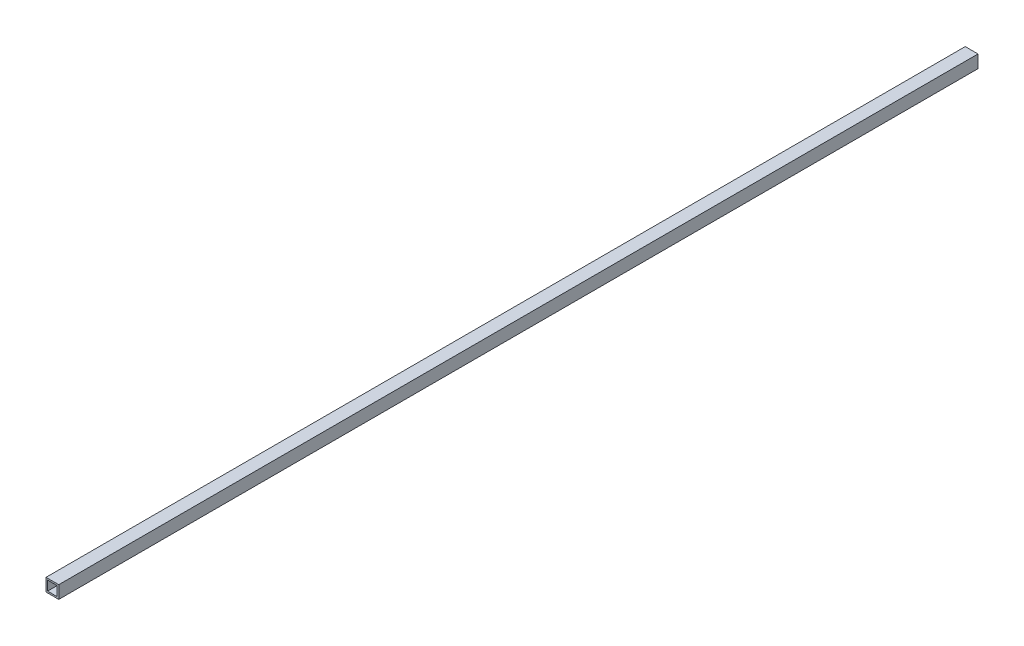
SolidWorks part; units mm, degrees
ref_plane "Front Plane" through (0, 0, 0) normal (0, 0, 1) x (1, 0, 0)
ref_plane "Top Plane" through (0, 0, 0) normal (0, 1, 0) x (1, 0, 0)
ref_plane "Right Plane" through (0, 0, 0) normal (1, 0, 0) x (0, 0, -1)
sketch "Sketch1" plane through (0, 0, 0) normal (0, 0, 1) x (1, 0, 0)
  line L0 (-4.7625, 4.7625) -> (4.7625, 4.7625)
  line L2 (-6.35, 6.35) -> (6.35, 6.35)
  line L3 (-6.35, 6.35) -> (-6.35, -6.35)
  line L4 (-6.35, -6.35) -> (6.35, -6.35)
  line L5 (6.35, 6.35) -> (6.35, -6.35)
  line L10 (4.7625, 4.7625) -> (4.7625, -4.7625)
  line L11 (-4.7625, -4.7625) -> (4.7625, -4.7625)
  line L12 (-4.7625, 4.7625) -> (-4.7625, -4.7625)
  point P12 (0, 6.35)
  point P14 (6.35, 0)
  dimension "Wall Thickness" = 1.5875
  dimension "Outside Width" = 12.7
  dimension "Outside Height" = 12.7
  dimension "Inside Height" = 9.525
  dimension "Inside Width" = 9.525
sketch "Sketch2" plane through (0, 0, 0) normal (1, 0, 0) x (0, 0, -1)
  line L0 (457.2, 0) -> (-457.2, 0)
  point P4 (0, 0)
  point P7 (-457.2, 0)
  point P10 (457.2, 0)
  dimension "Length" = 914.4
sketch "Sketch3" plane through (0, 0, 0) normal (0, 0, 1) x (1, 0, 0)
  line L21 (6.35, 6.35) -> (-6.35, 6.35)
  line L22 (6.35, -6.35) -> (6.35, 6.35)
  line L23 (-6.35, -6.35) -> (6.35, -6.35)
  line L24 (-6.35, 6.35) -> (-6.35, -6.35)
  line L25 (6.35, 6.35) -> (-6.35, 6.35)
  line L26 (6.35, -6.35) -> (6.35, 6.35)
  line L27 (-6.35, -6.35) -> (6.35, -6.35)
  line L28 (-6.35, 6.35) -> (-6.35, -6.35)
  line L29 (4.7625, 4.7625) -> (-4.7625, 4.7625)
  line L30 (4.7625, -4.7625) -> (4.7625, 4.7625)
  line L31 (-4.7625, -4.7625) -> (4.7625, -4.7625)
  line L32 (-4.7625, 4.7625) -> (-4.7625, -4.7625)
  line L33 (4.7625, 4.7625) -> (-4.7625, 4.7625)
  line L34 (4.7625, -4.7625) -> (4.7625, 4.7625)
  line L35 (-4.7625, -4.7625) -> (4.7625, -4.7625)
  line L36 (-4.7625, 4.7625) -> (-4.7625, -4.7625)
  dimension "D1" = 0
  dimension "D2" = 0
extrude "Boss-Extrude1" add sketch "Sketch3" along normal up to vertex (457.2 mm away) and the other way up to vertex (457.2 mm away) up to point (0, 0, 457.2) other way up to point (0, 0, -457.2)
sketch "Drawing Reference" plane through (0, 0, 0) normal (1, 0, 0) x (0, 0, -1)
  line L0 (-457.2, 0) -> (457.2, 0) construction
  line L1 (0, -6.35) -> (0, 6.35) construction
  line L2 (-457.2, -6.35) -> (457.2, -6.35) construction
  line L5 (-457.2, 6.35) -> (457.2, 6.35) construction
  point P7 (-448.056, 0)
  point P8 (448.056, 0)
  dimension "D1" = 9.144
equation "\"D1@Drawing Reference\"=\"Outside Width@Sketch1\" * 0.72"
